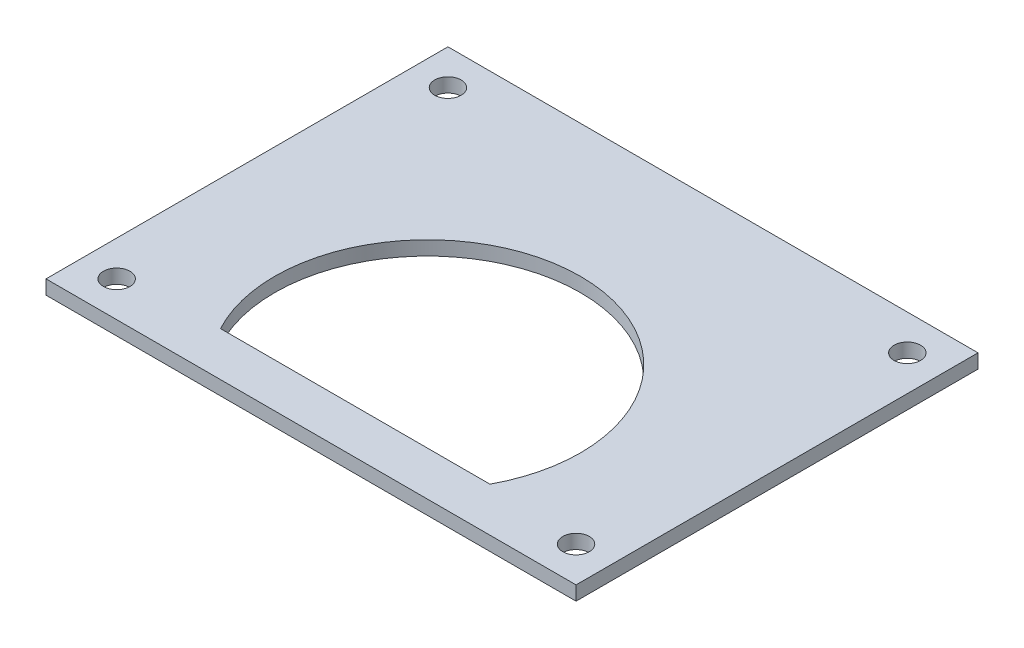
SolidWorks part; units mm, degrees
ref_plane "Front Plane" through (0, 0, 0) normal (0, 0, 1) x (1, 0, 0)
ref_plane "Top Plane" through (0, 0, 0) normal (0, 1, 0) x (1, 0, 0)
ref_plane "Right Plane" through (0, 0, 0) normal (1, 0, 0) x (0, 0, -1)
sketch "Sketch1" plane through (0, 0, 0) normal (0, 1, 0) x (1, 0, 0)
  line L1 (0, -9.7609) -> (0, 14.9403) construction
  line L2 (-15.25, -8.19) -> (15.25, -8.19)
  line L5 (-30, -13.19) -> (30, -13.19)
  line L6 (-30, -13.19) -> (-30, 32.31)
  line L7 (-30, 32.31) -> (30, 32.31)
  line L8 (30, -13.19) -> (30, 32.31)
  line L9 (-30, -13.19) -> (30, 32.31) construction
  line L10 (-30, 32.31) -> (30, -13.19) construction
  line L11 (-26, 28.31) -> (26, 28.31) construction
  line L12 (26, -9.19) -> (26, 28.31) construction
  line L13 (-26, -9.19) -> (26, -9.19) construction
  line L14 (-26, -9.19) -> (-26, 28.31) construction
  arc A1 (-15.25, -8.19) -> (15.25, -8.19) centre (0, 0) cw
  circle A2 centre (-26, 28.31) radius 1.5
  circle A3 centre (26, 28.31) radius 1.5
  circle A4 centre (-26, -9.19) radius 1.5
  circle A5 centre (26, -9.19) radius 1.5
  point P5 (0, -8.19)
  point P6 (0, 17.31)
  point P7 (0, 9.56)
  dimension "D7" = 3
  dimension "D1" = 30.5
  dimension "D2" = 25.5
  dimension "D3" = 5
  dimension "D4" = 30
  dimension "D5" = 15
  dimension "D6" = 4
extrude "Boss-Extrude3" add sketch "Sketch1" along normal blind 1.6
